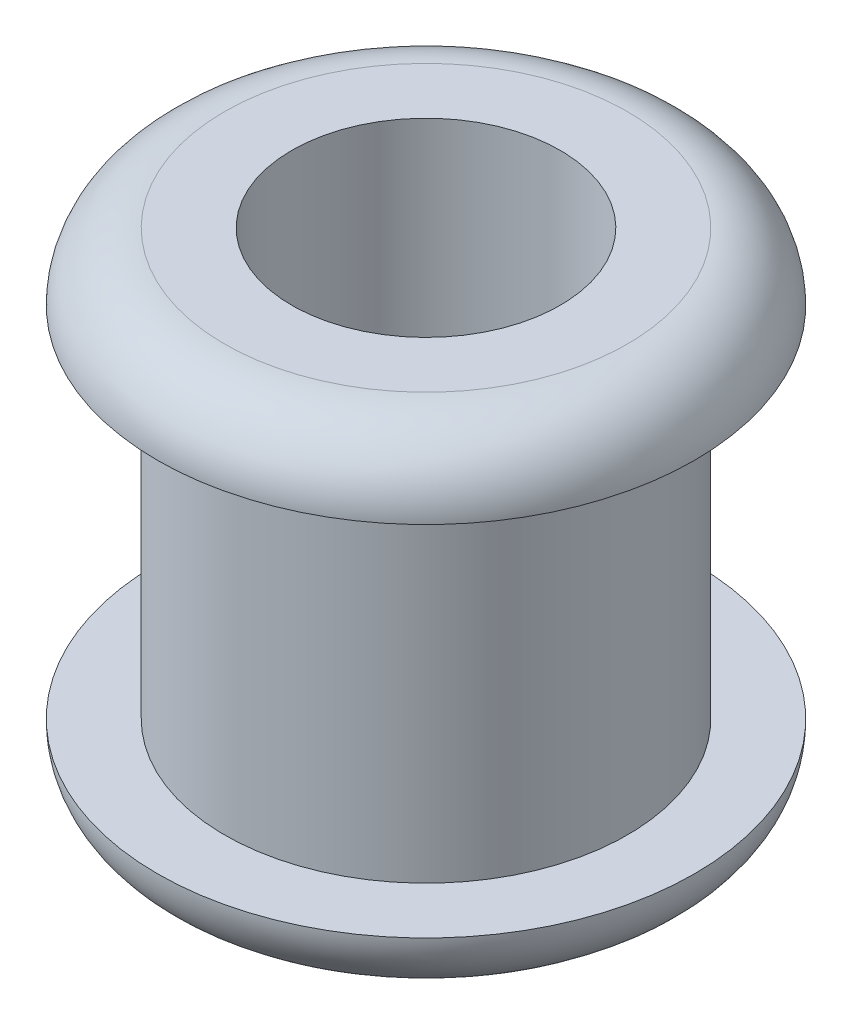
SolidWorks part; units mm, degrees
material "Rubber"
ref_plane "Front Plane" through (0, 0, 0) normal (0, 0, 1) x (1, 0, 0)
ref_plane "Top Plane" through (0, 0, 0) normal (0, 1, 0) x (1, 0, 0)
ref_plane "Right Plane" through (0, 0, 0) normal (1, 0, 0) x (0, 0, -1)
sketch "Sketch1" plane through (0, 0, 0) normal (0, 0, 1) x (1, 0, 0)
  line L0 (0, 0) -> (0, -68.0833) construction
  line L1 (4.7625, 0) -> (4.7625, -17.4625)
  line L2 (4.7625, -17.4625) -> (7.1437, -17.4625)
  line L3 (9.525, -15.0813) -> (7.1437, -15.0813)
  line L4 (7.1437, -15.0813) -> (7.1437, -2.3813)
  line L5 (7.1437, -2.3813) -> (9.525, -2.3812)
  line L6 (4.7625, 0) -> (7.1437, 0)
  arc A0 (7.1437, -17.4625) -> (9.525, -15.0813) centre (7.1437, -15.0813) ccw
  arc A1 (9.525, -2.3812) -> (7.1437, 0) centre (7.1437, -2.3813) ccw
  dimension "D1" = 12.7
  dimension "D2" = 9.525
  dimension "D3" = 14.2875
  dimension "D4" = 19.05
revolve "Revolve1" add sketch "Sketch1" angle 360 about L0
